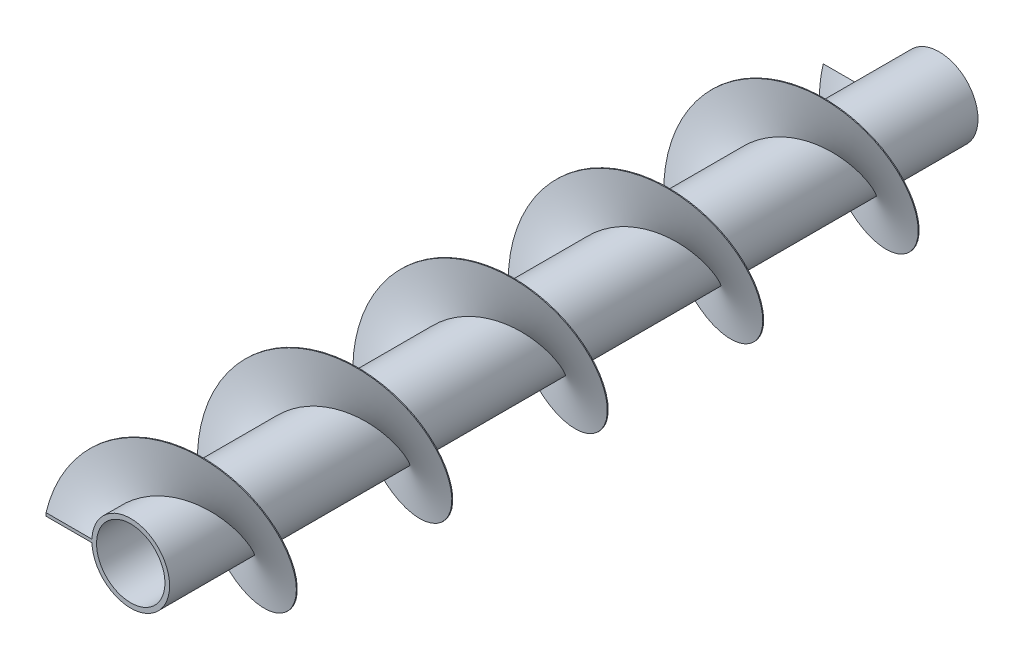
SolidWorks part; units mm, degrees
ref_plane "Plano frontal" through (0, 0, 0) normal (0, 0, 1) x (1, 0, 0)
ref_plane "Plano superior" through (0, 0, 0) normal (0, 1, 0) x (1, 0, 0)
ref_plane "Plano direito" through (0, 0, 0) normal (1, 0, 0) x (0, 0, -1)
sketch "Esboço1" plane through (0, 0, 0) normal (0, 0, 1) x (1, 0, 0)
  circle A0 centre (0, 0) radius 22
  circle A1 centre (0, 0) radius 25
  dimension "D1" = 50
  dimension "D2" = 3
extrude "Ressalto-extrusão1" add sketch "Esboço1" along normal blind 520
sketch "Esboço2" plane through (0, 0, 520) normal (0, 0, 1) x (1, 0, 0)
  circle A0 centre (0, 0) radius 25
  dimension "D1" = 50
curve "Hélice/Espiral1" pitch 100 height 500 turns 5
sketch "Esboço3" plane through (0, 0, 520) normal (0, 0, 1) x (1, 0, 0)
  line L0 (0, 0) -> (-26.5184, 0) construction
  line L1 (-24.5, 1) -> (-54.5, 1)
  line L2 (-24.5, 1) -> (-24.5, -1)
  line L3 (-24.5, -1) -> (-54.5, -1)
  line L4 (-54.5, 1) -> (-54.5, -1)
  dimension "D1" = 2
  dimension "D2" = 24.5
  dimension "D3" = 30
sweep "Varredura1" add profiles "Esboço3" path "Hélice/Espiral1"
